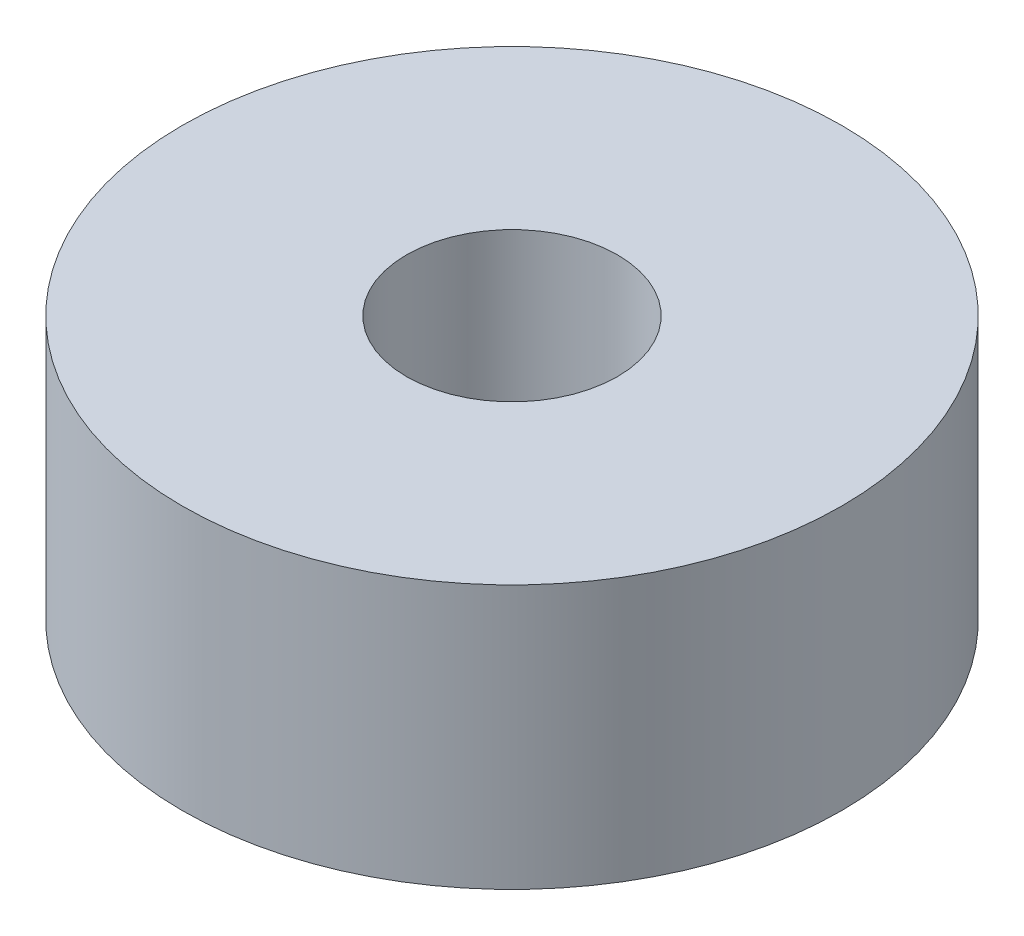
SolidWorks part; units mm, degrees
ref_plane "前视基准面" through (0, 0, 0) normal (0, 0, 1) x (1, 0, 0)
ref_plane "上视基准面" through (0, 0, 0) normal (0, 1, 0) x (1, 0, 0)
ref_plane "右视基准面" through (0, 0, 0) normal (1, 0, 0) x (0, 0, -1)
other "Configuration Table"
sketch "草图1" plane through (0, 0, 0) normal (0, 1, 0) x (1, 0, 0)
  circle A0 centre (0, 0) radius 2.5
  dimension "D1" = 5
extrude "凸台-拉伸1" add sketch "草图1" along normal blind 2
sketch "草图2" plane through (0, 2, 0) normal (0, 1, 0) x (1, 0, 0)
  circle A0 centre (0, 0) radius 0.8
  dimension "D1" = 1.6
extrude "切除-拉伸1" cut sketch "草图2" against normal through all contours A0
